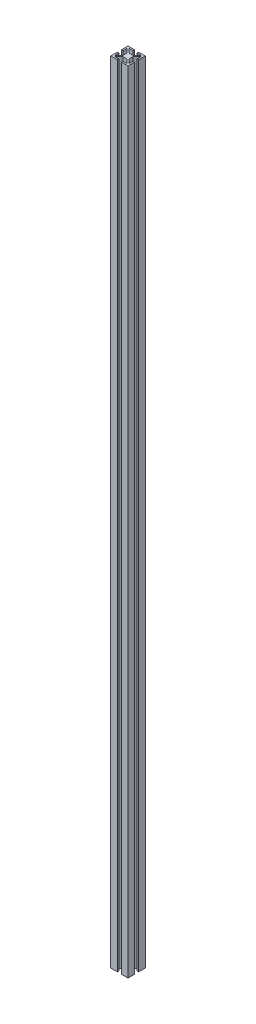
SolidWorks part; units mm, degrees
ref_plane "Front Plane" through (0, 0, 0) normal (0, 0, 1) x (1, 0, 0)
ref_plane "Top Plane" through (0, 0, 0) normal (0, 1, 0) x (1, 0, 0)
ref_plane "Right Plane" through (0, 0, 0) normal (1, 0, 0) x (0, 0, -1)
sketch "Sketch1" plane through (11.365, 0, 9.8462) normal (0, 1, 0) x (1, 0, 0)
  line L0 (-11.365, 9.8462) -> (-11.365, 32.3924) construction
  line L1 (-11.365, 9.8462) -> (-35.43, 9.8462) construction
  line L2 (-11.365, 9.8462) -> (-7.5972, 6.0784) construction
  line L3 (-24.065, 22.5462) -> (-14.2298, 22.5462)
  line L4 (-14.2298, 22.5462) -> (-14.2298, 20.3364)
  line L5 (-14.2298, 20.3364) -> (-20.2926, 20.3364)
  line L6 (-20.2926, 20.3364) -> (-14.3109, 14.3547)
  line L7 (-14.3109, 14.3547) -> (-8.4191, 14.3547)
  line L8 (-15.8735, 12.7921) -> (-15.8735, 6.9003)
  line L9 (-21.8552, 18.7738) -> (-15.8735, 12.7921)
  line L10 (-21.8552, 12.711) -> (-21.8552, 18.7738)
  line L11 (-24.065, 12.711) -> (-21.8552, 12.711)
  line L12 (-24.065, 22.5462) -> (-24.065, 12.711)
  line L13 (-14.3109, 5.3377) -> (-8.4191, 5.3377)
  line L14 (-20.2926, -0.644) -> (-14.3109, 5.3377)
  line L15 (-21.8552, 0.9186) -> (-15.8735, 6.9003)
  line L16 (-21.8552, 6.9814) -> (-21.8552, 0.9186)
  line L17 (-24.065, 6.9814) -> (-21.8552, 6.9814)
  line L18 (-24.065, -2.8538) -> (-24.065, 6.9814)
  line L19 (-14.2298, -0.644) -> (-20.2926, -0.644)
  line L20 (-14.2298, -2.8538) -> (-14.2298, -0.644)
  line L21 (-24.065, -2.8538) -> (-14.2298, -2.8538)
  line L22 (1.335, -2.8538) -> (-8.5002, -2.8538)
  line L23 (-8.5002, -2.8538) -> (-8.5002, -0.644)
  line L24 (-8.5002, -0.644) -> (-2.4374, -0.644)
  line L25 (1.335, -2.8538) -> (1.335, 6.9814)
  line L26 (1.335, 6.9814) -> (-0.8748, 6.9814)
  line L27 (-0.8748, 6.9814) -> (-0.8748, 0.9186)
  line L28 (-0.8748, 0.9186) -> (-6.8565, 6.9003)
  line L29 (-2.4374, -0.644) -> (-8.4191, 5.3377)
  line L30 (1.335, 22.5462) -> (1.335, 12.711)
  line L31 (1.335, 12.711) -> (-0.8748, 12.711)
  line L32 (-0.8748, 12.711) -> (-0.8748, 18.7738)
  line L33 (-0.8748, 18.7738) -> (-6.8565, 12.7921)
  line L34 (-6.8565, 12.7921) -> (-6.8565, 6.9003)
  line L35 (-2.4374, 20.3364) -> (-8.4191, 14.3547)
  line L36 (-8.5002, 20.3364) -> (-2.4374, 20.3364)
  line L37 (-8.5002, 22.5462) -> (-8.5002, 20.3364)
  line L38 (1.335, 22.5462) -> (-8.5002, 22.5462)
  point P20 (-15.8735, 9.8462)
  point P26 (-6.8565, 9.8462)
  point P36 (-11.365, 5.3377)
  point P42 (-11.365, 14.3547)
  dimension "D1" = 9.8352
  dimension "D2" = 12.7
  dimension "D3" = 4.5085
  dimension "D4" = 2.2098
  dimension "D5" = 1.1049
extrude "Boss-Extrude1" add sketch "Sketch1" along normal offset from surface (1163.0025 mm away) 30.48
other "1010<1>"
